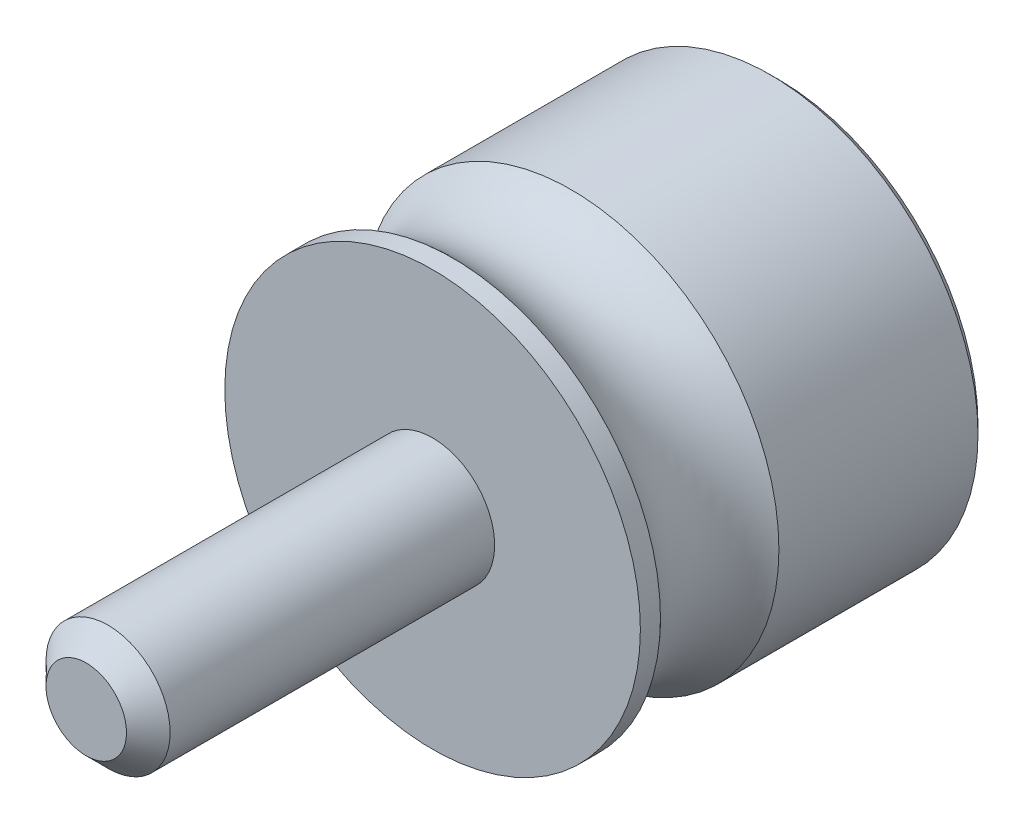
SolidWorks part; units mm, degrees
ref_plane "Front Plane" through (0, 0, 0) normal (0, 0, 1) x (1, 0, 0)
ref_plane "Top Plane" through (0, 0, 0) normal (0, 1, 0) x (1, 0, 0)
ref_plane "Right Plane" through (0, 0, 0) normal (1, 0, 0) x (0, 0, -1)
sketch "Sketch1" plane through (0, 0, 0) normal (0, 0, 1) x (1, 0, 0)
  circle A0 centre (0, 0) radius 4.7625
  dimension "D1" = 9.525
extrude "Boss-Extrude1" add sketch "Sketch1" along normal blind 4.7625
sketch "Sketch2" plane through (0, 0, 0) normal (0, 1, 0) x (1, 0, 0)
  line L0 (-4.7625, -7.4772) -> (-4.7625, -7.9375)
  line L1 (-4.7625, -7.9375) -> (0, -7.9375)
  line L2 (0, -7.9375) -> (0, -4.7625)
  line L3 (-4.7625, -4.7625) -> (4.7625, -4.7625) construction
  line L4 (0, -4.7625) -> (-4.7625, -4.7625)
  arc A0 (-4.7625, -4.7625) -> (-4.7625, -7.4772) centre (-6.1198, -6.1198) cw
  dimension "D1" = 3.175
revolve "Revolve1" add sketch "Sketch2" angle 360 about L2
sketch "Sketch3" plane through (0, 0, 7.9375) normal (0, 0, 1) x (1, 0, 0)
  circle A0 centre (0, 0) radius 1.4224
  dimension "D1" = 2.8448
extrude "Boss-Extrude2" add sketch "Sketch3" along normal blind 7.9375
chamfer "Chamfer1" distance 0.2 angle 45 1 edges at (4.7625, 0, 0)
chamfer "Chamfer2" distance 0.5 angle 45 1 edges at (1.4224, 0, 15.875)
